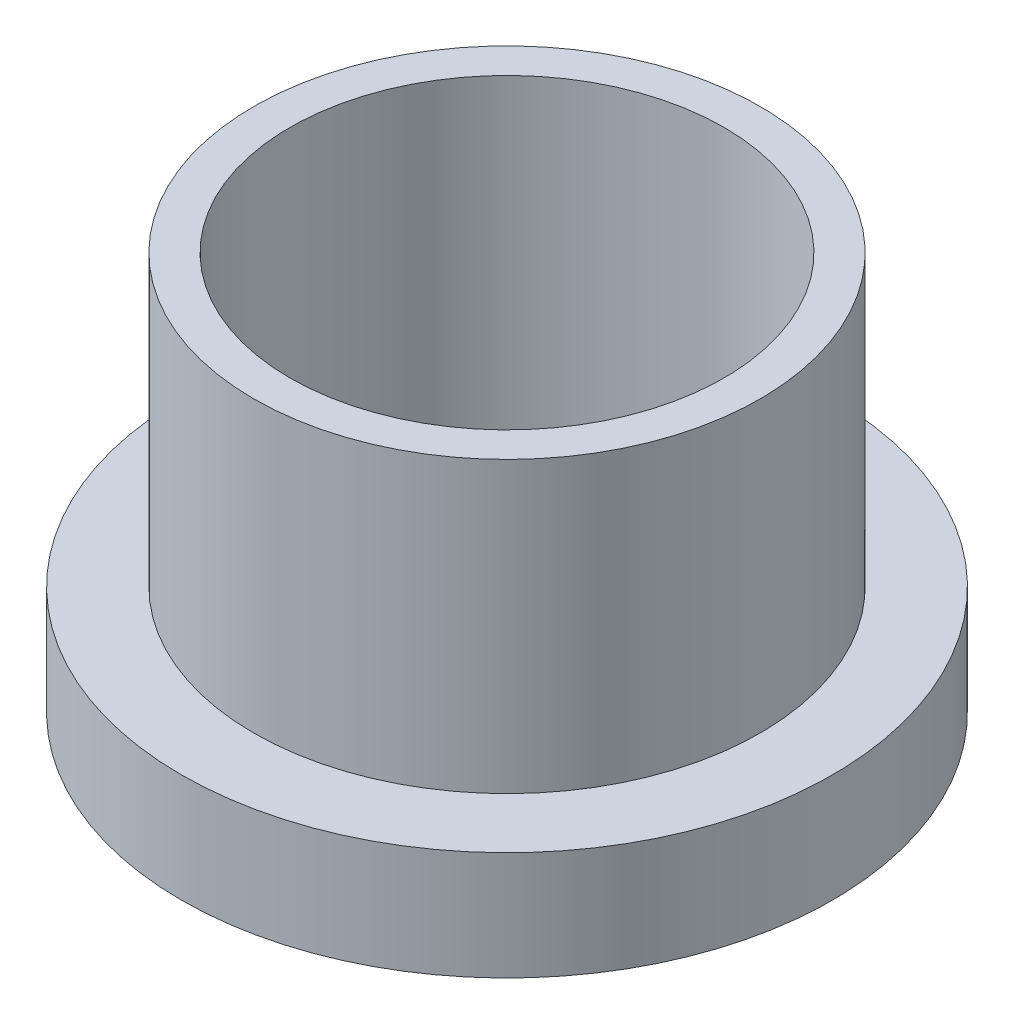
SolidWorks part; units mm, degrees
ref_plane "Ön Düzlem" through (0, 0, 0) normal (0, 0, 1) x (1, 0, 0)
ref_plane "Üst Düzlem" through (0, 0, 0) normal (0, 1, 0) x (1, 0, 0)
ref_plane "Sağ Düzlem" through (0, 0, 0) normal (1, 0, 0) x (0, 0, -1)
sketch "Sketch1" plane through (0, 0, 0) normal (0, 1, 0) x (1, 0, 0)
  circle A0 centre (0, 0) radius 9
  dimension "D1" = 18
extrude "Boss-Extrude1" add sketch "Sketch1" along normal blind 3
sketch "Sketch2" plane through (0, 3, 0) normal (0, 1, 0) x (1, 0, 0)
  circle A0 centre (0, 0) radius 7
  dimension "D1" = 14
extrude "Boss-Extrude2" add sketch "Sketch2" along normal blind 8
sketch "Sketch3" plane through (0, 11, 0) normal (0, 1, 0) x (1, 0, 0)
  circle A0 centre (0, 0) radius 6
  dimension "D1" = 12
extrude "Cut-Extrude1" cut sketch "Sketch3" against normal through all
